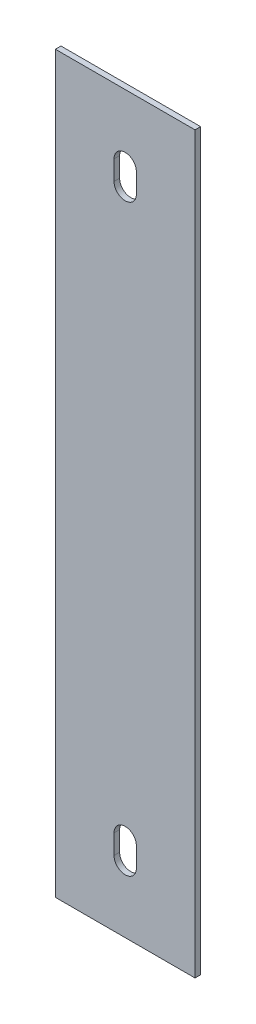
SolidWorks part; units mm, degrees
ref_plane "Front Plane" through (0, 0, 0) normal (0, 0, 1) x (1, 0, 0)
ref_plane "Top Plane" through (0, 0, 0) normal (0, 1, 0) x (1, 0, 0)
ref_plane "Right Plane" through (0, 0, 0) normal (1, 0, 0) x (0, 0, -1)
sketch "Sketch1" plane through (0, 0, 0) normal (0, 0, 1) x (1, 0, 0)
  line L1 (25, -131.5) -> (-25, -131.5)
  line L2 (25, -131.5) -> (25, 131.5)
  line L3 (25, 131.5) -> (-25, 131.5)
  line L4 (-25, -131.5) -> (-25, 131.5)
  line L5 (25, -131.5) -> (-25, 131.5) construction
  line L6 (25, 131.5) -> (-25, -131.5) construction
  point P0 (0, 0)
  dimension "D1" = 263
  dimension "D2" = 50
extrude "Boss-Extrude1" add sketch "Sketch1" along normal blind 2
sketch "Sketch2" plane through (0, 0, 2) normal (0, 0, 1) x (1, 0, 0)
  line L0 (0, -108) -> (0, -101) construction
  line L1 (-4, -108) -> (-4, -101)
  line L2 (4, -108) -> (4, -101)
  line L3 (-25, -131.5) -> (25, -131.5) construction
  line L4 (0, 0) -> (-26.5418, 0) construction
  line L5 (0, 108) -> (0, 101) construction
  line L6 (-4, 108) -> (-4, 101)
  line L7 (4, 108) -> (4, 101)
  arc A0 (-4, -108) -> (4, -108) centre (0, -108) ccw
  arc A1 (4, -101) -> (-4, -101) centre (0, -101) ccw
  arc A2 (-4, 108) -> (4, 108) centre (0, 108) cw
  arc A3 (4, 101) -> (-4, 101) centre (0, 101) cw
  point P3 (0, -104.5)
  point P8 (0, -97)
  point P9 (0, -112)
  point P16 (0, 104.5)
  dimension "D1" = 15
  dimension "D2" = 27
  dimension "D3" = 8
extrude "Cut-Extrude1" cut sketch "Sketch2" against normal through all
